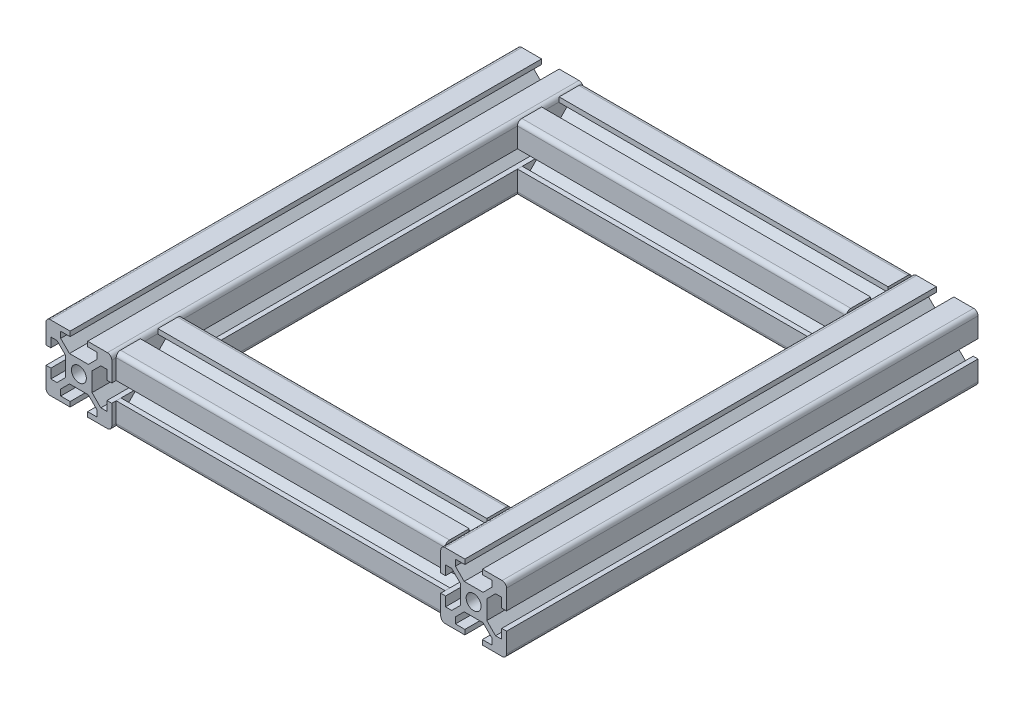
SolidWorks part; units mm, degrees
ref_plane "Front Plane" through (0, 0, 0) normal (0, 0, 1) x (1, 0, 0)
ref_plane "Top Plane" through (0, 0, 0) normal (0, 1, 0) x (1, 0, 0)
ref_plane "Right Plane" through (0, 0, 0) normal (1, 0, 0) x (0, 0, -1)
sketch3d "3DSketch1"
  line L0 (90, 0, 0) -> (-90, 0, 0)
  line L1 (-90, 0, 17) -> (-90, 0, -183)
  line L2 (90, 0, 17) -> (90, 0, -183)
  line L3 (-90, 0, -183) -> (90, 0, -183)
  line L4 (-90, 0, 17) -> (90, 0, 17) construction
  point P4 (0, 0, 0)
  dimension "D1" = 17
  dimension "D2" = 200
  dimension "D3" = 180
other "Aluminium extrusion 3030(1)"
ref_plane "Plane1" through (-90, 0, 17) normal (0, 0, -1) x (1, 0, 0)
sketch "Sketch1" plane through (-90, 0, 17) normal (0, 0, -1) x (1, 0, 0)
  line L0 (0, 0) -> (-21.5122, 0) construction
  line L1 (0, 0) -> (0, 25.7819) construction
  line L2 (0, 6) -> (-4.3029, 6)
  line L3 (-4.3029, 6) -> (-8.3, 9.9971)
  line L4 (-8.3, 12.8) -> (-4, 12.8)
  line L5 (-8.3, 9.9971) -> (-8.3, 12.8)
  line L6 (-4, 12.8) -> (-4, 15)
  line L7 (-4, 15) -> (-13, 15)
  line L8 (-14.4142, 14.4142) -> (0, 0) construction
  line L9 (-6, 0) -> (-6, 4.3029)
  line L10 (-6, 4.3029) -> (-9.9971, 8.3)
  line L11 (-9.9971, 8.3) -> (-12.8, 8.3)
  line L12 (-12.8, 8.3) -> (-12.8, 4)
  line L13 (-12.8, 4) -> (-15, 4)
  line L14 (-15, 4) -> (-15, 13)
  line L15 (6, 0) -> (6, 4.3029)
  line L16 (6, 4.3029) -> (9.9971, 8.3)
  line L17 (9.9971, 8.3) -> (12.8, 8.3)
  line L18 (12.8, 8.3) -> (12.8, 4)
  line L19 (12.8, 4) -> (15, 4)
  line L20 (15, 4) -> (15, 13)
  line L21 (4, 15) -> (13, 15)
  line L22 (4, 12.8) -> (4, 15)
  line L23 (8.3, 12.8) -> (4, 12.8)
  line L24 (8.3, 9.9971) -> (8.3, 12.8)
  line L25 (4.3029, 6) -> (8.3, 9.9971)
  line L26 (0, 6) -> (4.3029, 6)
  line L27 (0, -6) -> (4.3029, -6)
  line L28 (4.3029, -6) -> (8.3, -9.9971)
  line L29 (8.3, -9.9971) -> (8.3, -12.8)
  line L30 (8.3, -12.8) -> (4, -12.8)
  line L31 (4, -12.8) -> (4, -15)
  line L32 (4, -15) -> (13, -15)
  line L33 (15, -4) -> (15, -13)
  line L34 (12.8, -4) -> (15, -4)
  line L35 (12.8, -8.3) -> (12.8, -4)
  line L36 (9.9971, -8.3) -> (12.8, -8.3)
  line L37 (6, -4.3029) -> (9.9971, -8.3)
  line L38 (6, 0) -> (6, -4.3029)
  line L39 (-6, 0) -> (-6, -4.3029)
  line L40 (-6, -4.3029) -> (-9.9971, -8.3)
  line L41 (-9.9971, -8.3) -> (-12.8, -8.3)
  line L42 (-12.8, -8.3) -> (-12.8, -4)
  line L43 (-12.8, -4) -> (-15, -4)
  line L44 (-15, -4) -> (-15, -13)
  line L45 (-4, -15) -> (-13, -15)
  line L46 (-4, -12.8) -> (-4, -15)
  line L47 (-8.3, -12.8) -> (-4, -12.8)
  line L48 (-8.3, -9.9971) -> (-8.3, -12.8)
  line L49 (-4.3029, -6) -> (-8.3, -9.9971)
  line L50 (0, -6) -> (-4.3029, -6)
  circle A0 centre (0, 0) radius 3.4
  arc A1 (-13, 15) -> (-15, 13) centre (-13, 13) ccw
  arc A2 (15, 13) -> (13, 15) centre (13, 13) ccw
  arc A3 (13, -15) -> (15, -13) centre (13, -13) ccw
  arc A4 (-15, -13) -> (-13, -15) centre (-13, -13) ccw
  point P0 (0, 0)
  point P3 (0, 0)
  point P70 (0, 0)
  dimension "D1" = 6.8
  dimension "D7" = 1.2
  dimension "D8" = 2
  dimension "D2" = 45
  dimension "D3" = 15
  dimension "D4" = 9
  dimension "D5" = 8.3
  dimension "D6" = 4
  dimension "D9" = 2.2
